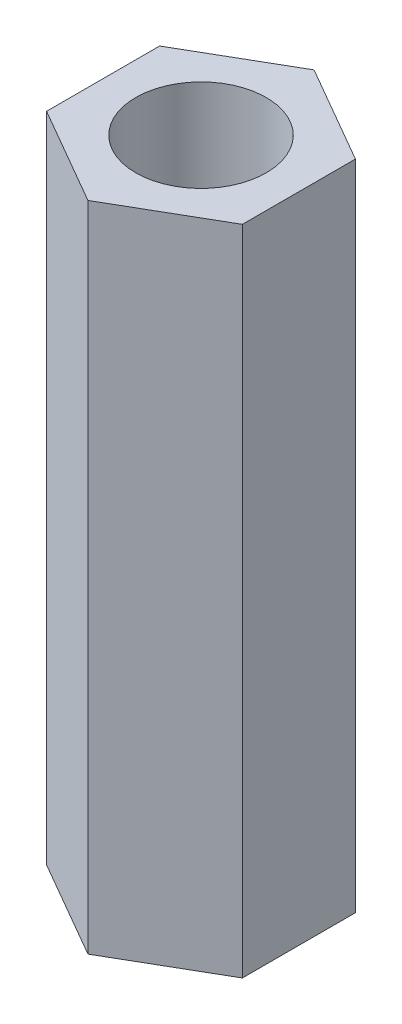
SolidWorks part; units mm, degrees
ref_plane "Front Plane" through (0, 0, 0) normal (0, 0, 1) x (1, 0, 0)
ref_plane "Top Plane" through (0, 0, 0) normal (0, 1, 0) x (1, 0, 0)
ref_plane "Right Plane" through (0, 0, 0) normal (1, 0, 0) x (0, 0, -1)
sketch "Sketch1" plane through (0, 0, 0) normal (0, 1, 0) x (1, 0, 0)
  line L1 (0, 2.5981) -> (-2.25, 1.299)
  line L2 (-2.25, 1.299) -> (-2.25, -1.299)
  line L3 (-2.25, -1.299) -> (0, -2.5981)
  line L4 (0, -2.5981) -> (2.25, -1.299)
  line L5 (2.25, -1.299) -> (2.25, 1.299)
  line L6 (2.25, 1.299) -> (0, 2.5981)
  circle A0 centre (0, 0) radius 2.25 construction
  dimension "D1" = 4.5
extrude "Boss-Extrude1" add sketch "Sketch1" along normal blind 15
sketch "Sketch2" plane through (0, 15, 0) normal (0, 1, 0) x (1, 0, 0)
  circle A0 centre (0, 0) radius 1.5
  dimension "D1" = 3
extrude "Cut-Extrude1" cut sketch "Sketch2" against normal through all
